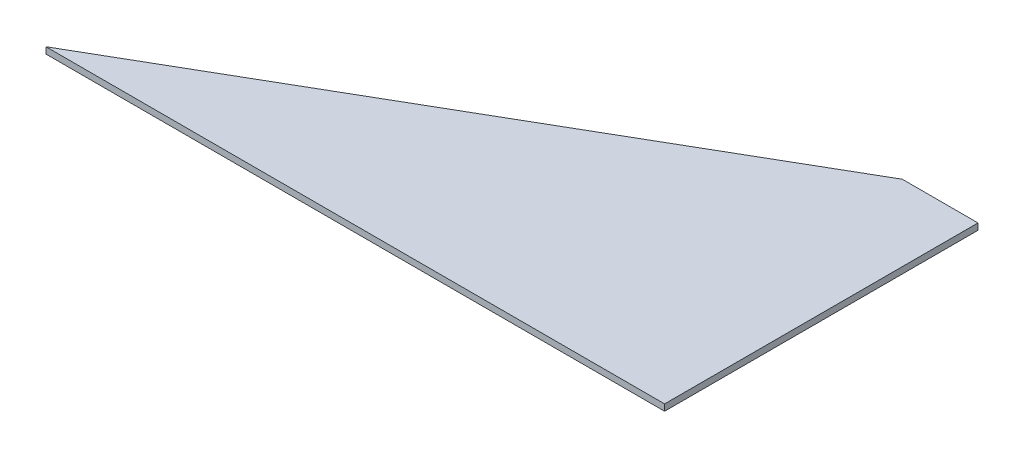
SolidWorks part; units mm, degrees
material "Hexcel AS4C (3000 Filaments)"
ref_plane "Front" through (0, 0, 0) normal (0, 0, 1) x (1, 0, 0)
ref_plane "Top" through (0, 0, 0) normal (0, 1, 0) x (1, 0, 0)
ref_plane "Right" through (0, 0, 0) normal (1, 0, 0) x (0, 0, -1)
sketch "Sketch1" plane through (0, 0, 0) normal (0, 1, 0) x (1, 0, 0)
  line L0 (0, 0) -> (381, 0)
  line L1 (381, 0) -> (381, 193.04)
  line L2 (381, 193.04) -> (334.3551, 193.04)
  line L3 (334.3551, 193.04) -> (0, 0)
  dimension "D1" = 30
  dimension "D2" = 381
  dimension "D3" = 193.04
extrude "Boss-Extrude1" add sketch "Sketch1" along normal blind 3.937
ref_plane "Plane1" through (0, 1.9685, 0) normal (0, -1, 0) x (-1, 0, 0)
